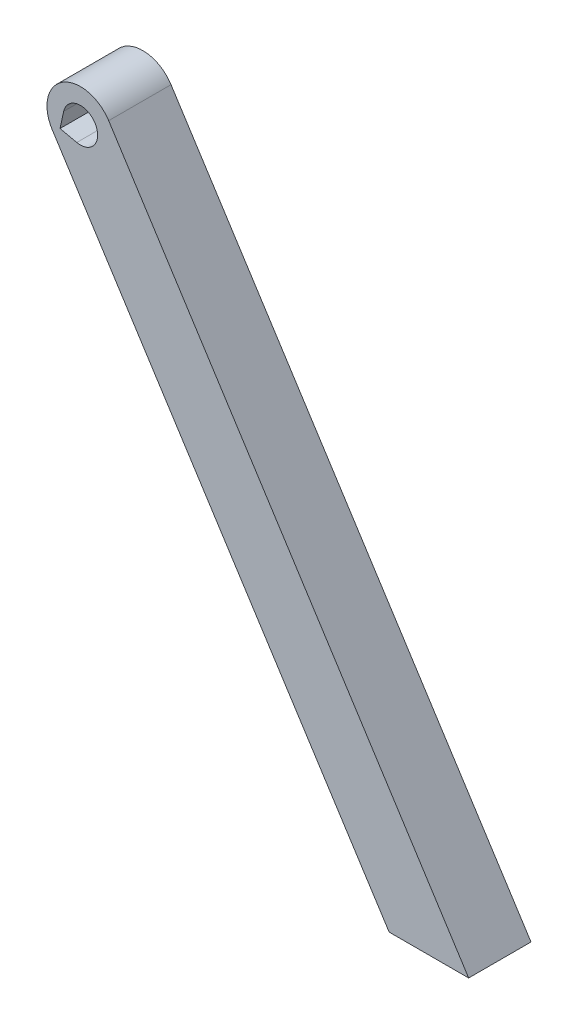
SolidWorks part; units mm, degrees
ref_plane "Alzado" through (0, 0, 0) normal (0, 0, 1) x (1, 0, 0)
ref_plane "Planta" through (0, 0, 0) normal (0, 1, 0) x (1, 0, 0)
ref_plane "Vista lateral" through (0, 0, 0) normal (1, 0, 0) x (0, 0, -1)
sketch "Croquis1" plane through (0, 0, 0) normal (0, 0, 1) x (1, 0, 0)
  line L1 (-74.2439, 54.649) -> (-34.4036, -7.6033)
  line L2 (-80.4878, 50.653) -> (-43.2048, -7.6033)
  line L3 (-34.4036, -7.6033) -> (-43.2048, -7.6033)
  line L4 (-79.6291, 51.2026) -> (-79.2217, 53.0584)
  line L7 (-77.7733, 50.7952) -> (-79.6291, 51.2026)
  arc A0 (-74.2439, 54.649) -> (-80.4878, 50.653) centre (-77.3659, 52.651) ccw
  arc A1 (-77.7733, 50.7952) -> (-79.2217, 53.0584) centre (-77.3659, 52.651) ccw
extrude "Saliente-Extruir1" add sketch "Croquis1" along normal blind 6.9
